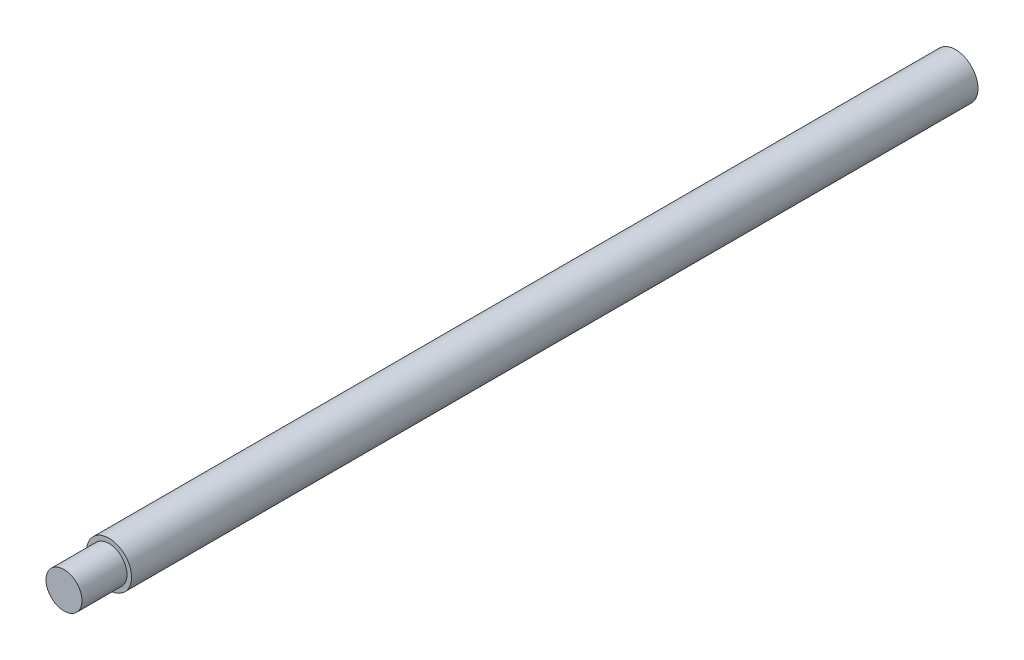
SolidWorks part; units mm, degrees
material "6063-T6"
ref_plane "Płaszczyzna przednia" through (0, 0, 0) normal (0, 0, 1) x (1, 0, 0)
ref_plane "Płaszczyzna górna" through (0, 0, 0) normal (0, 1, 0) x (1, 0, 0)
ref_plane "Płaszczyzna prawa" through (0, 0, 0) normal (1, 0, 0) x (0, 0, -1)
sketch "Sketch1" plane through (0, 0, 0) normal (0, 0, 1) x (1, 0, 0)
  circle A0 centre (0, 0) radius 5
  dimension "D1" = 10
extrude "Boss-Extrude1" add sketch "Sketch1" along normal blind 198
sketch "Szkic2" plane through (0, 0, 0) normal (0, 0, -1) x (-1, 0, 0)
  point P0 (0, 0)
sketch "Szkic5" plane through (0, 0, 0) normal (0, 0, -1) x (-1, 0, 0)
  point P0 (0, 0)
hole_wizard "Otwór gwintowany M52" positions "Szkic5" profile "Szkic6" tap size "M5" standard "DIN"
cosmetic thread "Oznaczenie gwintu2" parameters "D1"=20, "D2"=5
sketch "Szkic6" plane through (0, 0, 0) normal (1, 0, 0) x (0, 1, 0)
  line L0 (0, 0) -> (0, 21.2618)
  line L1 (0, 21.2618) -> (2.1, 20)
  line L2 (2.1, 20) -> (2.1, 0)
  line L5 (2.1, 0) -> (0, 0)
  line L10 (0, 21.2618) -> (-2.1, 20) construction
  line L11 (0, -6.35) -> (0, 107.95) construction
  dimension "Średnica wiertła gwintu" = 4.2
  dimension "Głębokość otworu gwintowanego" = 20
  dimension "Kąt wiertła" = 118
cosmetic thread "Gwint otworu1" parameters "D1"=20, "D2"=5.2
sketch "Szkic7" plane through (0, 0, 198) normal (0, 0, 1) x (1, 0, 0)
  circle A0 centre (0, 0) radius 4
  circle A1 centre (0, 0) radius 5.5
  dimension "D1" = 11
  dimension "D2" = 8
extrude "Wytnij-wyciągnięcie1" cut sketch "Szkic7" against normal blind 10
